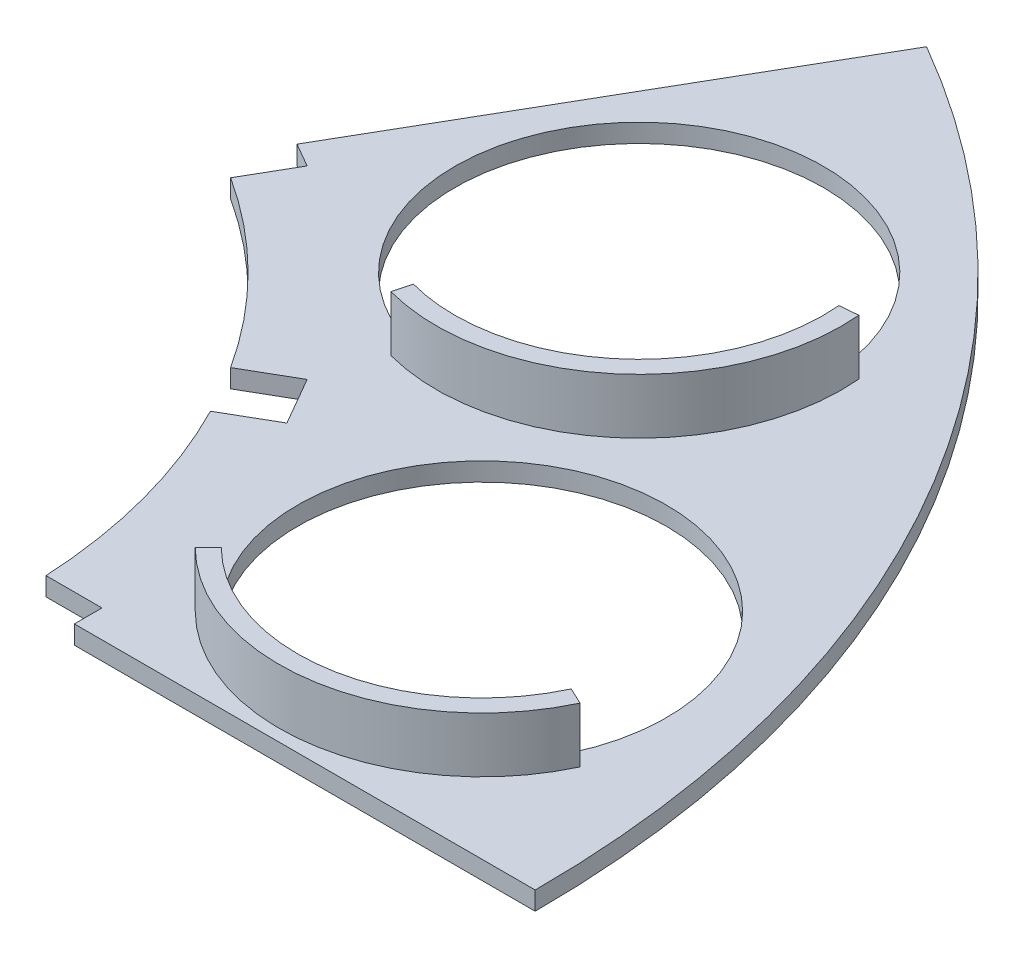
SolidWorks part; units mm, degrees
ref_plane "Ebene vorne" through (0, 0, 0) normal (0, 0, 1) x (1, 0, 0)
ref_plane "Ebene oben" through (0, 0, 0) normal (0, 1, 0) x (1, 0, 0)
ref_plane "Ebene rechts" through (0, 0, 0) normal (1, 0, 0) x (0, 0, -1)
sketch "Skizze1" plane through (0, 0, 0) normal (0, 1, 0) x (1, 0, 0)
  line L0 (150, 0) -> (290, 0)
  line L1 (0, 0) -> (154.7296, 267.9995) construction
  line L2 (75, 129.9038) -> (145, 251.1474)
  arc A0 (150, 0) -> (75, 129.9038) centre (0, 0) ccw
  arc A1 (290, 0) -> (145, 251.1474) centre (0, 0) ccw
  dimension "D1" = 290
  dimension "D2" = 150
  dimension "D3" = 60
extrude "Aufsatz-Linear austragen1" add sketch "Skizze1" along normal blind 5
sketch "Skizze2" plane through (0, 5, 0) normal (0, 1, 0) x (1, 0, 0)
  line L0 (145, 251.1474) -> (75, 129.9038) construction
  line L1 (150, 0) -> (290, 0) construction
  line L2 (0, 0) -> (217.3333, 58.2343) construction
  line L3 (0, 0) -> (159.099, 159.099) construction
  line L4 (150, 0) -> (290, 0) construction
  arc A0 (225, 0) -> (112.5, 194.8557) centre (0, 0) ccw construction
  circle A1 centre (217.3333, 58.2343) radius 50
  circle A2 centre (159.099, 159.099) radius 50
  dimension "D1" = 30
  dimension "D3" = 100
  dimension "D4" = 225
  dimension "D2" = 15
extrude "Schnitt-Linear austragen1" cut sketch "Skizze2" against normal through all
sketch "Skizze3" plane through (0, 5, 0) normal (0, 1, 0) x (1, 0, 0)
  line L0 (0, 0) -> (217.3333, 58.2343) construction
  line L1 (0, 0) -> (159.099, 159.099) construction
  line L2 (217.3333, 58.2343) -> (181.978, 22.8789) construction
  line L3 (217.3333, 58.2343) -> (262.6487, 37.1034) construction
  line L4 (159.099, 159.099) -> (208.9088, 163.4568) construction
  line L5 (159.099, 159.099) -> (146.1581, 110.8027) construction
  line L6 (146.1581, 110.8027) -> (144.864, 105.9731)
  line L7 (213.8897, 163.8926) -> (208.9088, 163.4568)
  line L8 (181.978, 22.8789) -> (178.4424, 19.3434)
  line L9 (262.6487, 37.1034) -> (267.1802, 34.9903)
  circle A0 centre (217.3333, 58.2343) radius 50 construction
  circle A1 centre (159.099, 159.099) radius 50 construction
  arc A2 (146.1581, 110.8027) -> (208.9088, 163.4568) centre (159.099, 159.099) ccw
  arc A3 (181.978, 22.8789) -> (262.6487, 37.1034) centre (217.3333, 58.2343) ccw
  arc A4 (178.4424, 19.3434) -> (267.1802, 34.9903) centre (217.3333, 58.2343) ccw
  arc A5 (144.864, 105.9731) -> (213.8897, 163.8926) centre (159.099, 159.099) ccw
  dimension "D1" = 30
  dimension "D2" = 110
  dimension "D3" = 110
  dimension "D4" = 30
  dimension "D5" = 5
extrude "Aufsatz-Linear austragen2" add sketch "Skizze3" along normal blind 15
sketch "Skizze4" plane through (0, 0, 0) normal (0, -1, 0) x (1, 0, 0)
  line L0 (150, 0) -> (290, 0) construction
  line L1 (145, -251.1474) -> (75, -129.9038) construction
  line L2 (0, 0) -> (277.6046, -36.5473) construction
  line L3 (0, 0) -> (258.6863, -107.1514) construction
  line L4 (0, 0) -> (222.1389, -170.4532) construction
  line L5 (0, 0) -> (170.4532, -222.1389) construction
  arc A0 (85, -147.2243) -> (170, 0) centre (0, 0) ccw construction
  arc A1 (140, -242.4871) -> (280, 0) centre (0, 0) ccw construction
  circle A2 centre (277.6046, -36.5473) radius 3.6
  circle A3 centre (258.6863, -107.1514) radius 3.6
  circle A4 centre (222.1389, -170.4532) radius 3.6
  circle A5 centre (170.4532, -222.1389) radius 3.6
  circle A6 centre (103.4894, -134.8701) radius 3.6
  circle A7 centre (134.8701, -103.4894) radius 3.6
  circle A9 centre (168.5456, -22.1895) radius 3.6
  circle A10 centre (157.0595, -65.0562) radius 3.6
  dimension "D1" = 170
  dimension "D2" = 280
  dimension "D7" = 7.2
  dimension "D3" = 15
  dimension "D4" = 15
  dimension "D5" = 15
  dimension "D6" = 7.5
extrude "Schnitt-Linear austragen2" cut sketch "Skizze4" against normal blind 4.4
sketch "Skizze5" plane through (0, 5, 0) normal (0, 1, 0) x (1, 0, 0)
  line L0 (0, 0) -> (290, 0) construction
  line L1 (0, 0) -> (145, 251.1474) construction
  line L2 (0, 0) -> (251.1474, 145) construction
  line L3 (75, 129.9038) -> (82.5, 142.8942)
  line L4 (150, 0) -> (165, 0)
  line L6 (149.8124, 7.5) -> (165, 7.5)
  line L7 (165, 0) -> (165, 7.5)
  line L8 (125.9913, 81.4014) -> (139.1442, 88.9952)
  line L9 (139.1442, 88.9952) -> (146.6442, 76.0048)
  line L10 (82.5, 142.8942) -> (88.9952, 139.1442)
  line L11 (88.9952, 139.1442) -> (81.4014, 125.9913)
  line L12 (146.6442, 76.0048) -> (133.4913, 68.411)
  arc A0 (290, 0) -> (145, 251.1474) centre (0, 0) ccw construction
  arc A1 (165, 0) -> (82.5, 142.8942) centre (0, 0) ccw construction
  arc A2 (150, 0) -> (75, 129.9038) centre (0, 0) ccw construction
  arc A4 (150, 0) -> (149.8124, 7.5) centre (0, 0) ccw
  arc A5 (81.4014, 125.9913) -> (75, 129.9038) centre (0, 0) ccw
  arc A6 (133.4913, 68.411) -> (125.9913, 81.4014) centre (0, 0) ccw
  point P16 (157.5, 3.75)
  point P28 (142.8942, 82.5)
  dimension "D1" = 165
  dimension "D3" = 15
  dimension "D2" = 7.5
extrude "Schnitt-Linear austragen3" cut sketch "Skizze5" against normal through all
